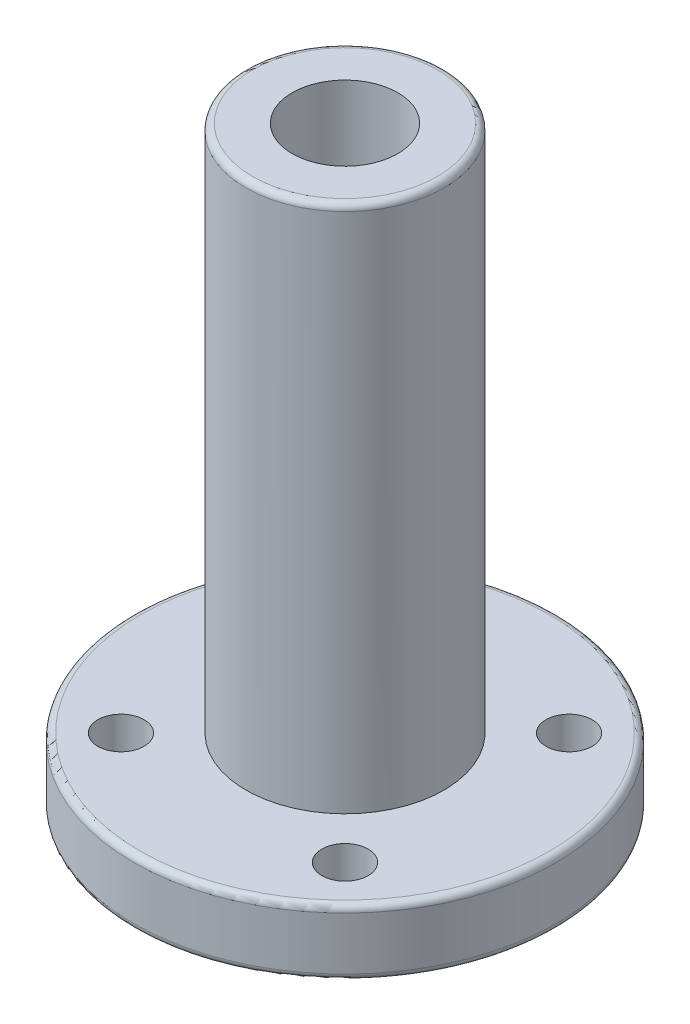
SolidWorks part; units mm, degrees
ref_plane "Front Plane" through (0, 0, 0) normal (0, 0, 1) x (1, 0, 0)
ref_plane "Top Plane" through (0, 0, 0) normal (0, 1, 0) x (1, 0, 0)
ref_plane "Right Plane" through (0, 0, 0) normal (1, 0, 0) x (0, 0, -1)
sketch "Sketch1" plane through (0, 0, 0) normal (0, 1, 0) x (1, 0, 0)
  circle A0 centre (0, 0) radius 7.5
  circle A1 centre (0, 0) radius 4
  dimension "D1" = 8
  dimension "D2" = 15
extrude "Boss-Extrude1" add sketch "Sketch1" along normal blind 45
sketch "Sketch2" plane through (0, 0, 0) normal (0, -1, 0) x (1, 0, 0)
  line L0 (0, 0) -> (0, 11.1142) construction
  line L1 (-12.5, 12.5) -> (12.5, 12.5) construction
  line L2 (-12.5, 12.5) -> (-12.5, -12.5) construction
  line L3 (-12.5, -12.5) -> (12.5, -12.5) construction
  line L4 (12.5, 12.5) -> (12.5, -12.5) construction
  line L5 (0, 0) -> (11.2445, 0) construction
  line L6 (0, 0) -> (8.4853, 8.4853) construction
  circle A0 centre (8.4853, 8.4853) radius 1.75
  circle A1 centre (0, 0) radius 7.5 construction
  circle A2 centre (0, 0) radius 7.5
  circle A3 centre (-8.4853, 8.4853) radius 1.75
  circle A4 centre (-8.4853, -8.4853) radius 1.75
  circle A5 centre (8.4853, -8.4853) radius 1.75
  circle A6 centre (0, 0) radius 16
  circle A7 centre (0, 0) radius 12 construction
  point P8 (-12.5, 0)
  point P9 (0, 12.5)
  dimension "D1" = 25
  dimension "D2" = 3.5
  dimension "D4" = 24
  dimension "D3" = 32
  dimension "D5" = 45
extrude "Boss-Extrude2" add sketch "Sketch2" against normal blind 5
fillet "Fillet2" radius 0.5 3 edges at (0, 0, -16) (0, 45, 7.5) (0, 5, -16)
